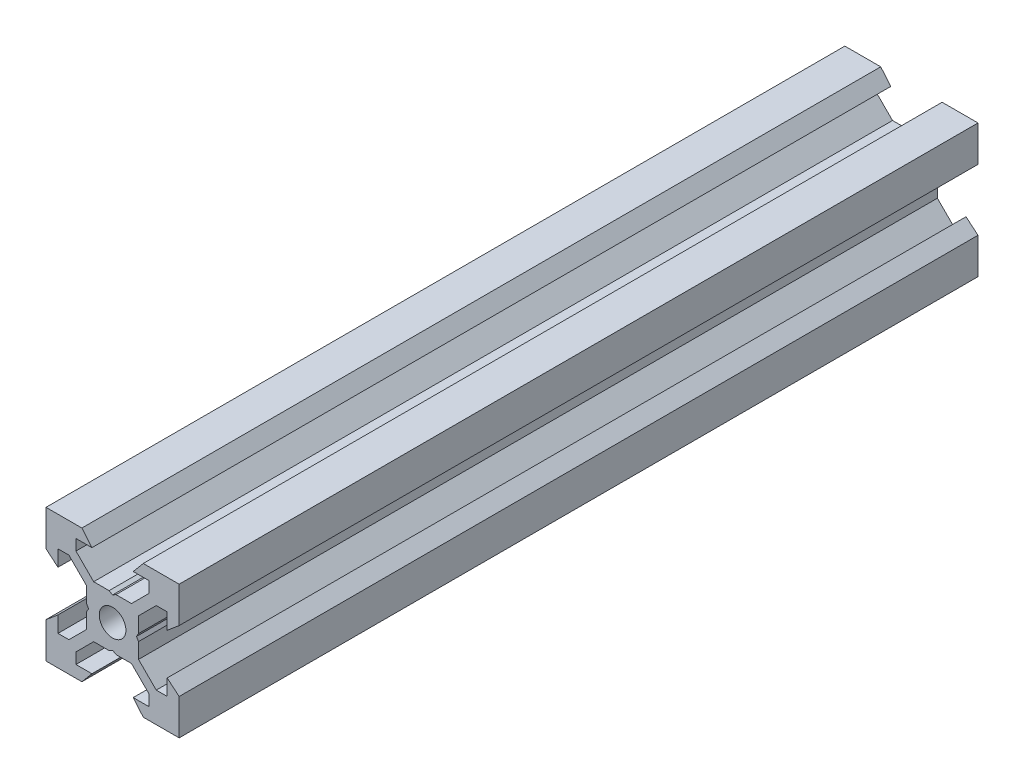
SolidWorks part; units mm, degrees
material "6063-O"
ref_plane "Front Plane" through (0, 0, 0) normal (0, 0, 1) x (1, 0, 0)
ref_plane "Top Plane" through (0, 0, 0) normal (0, 1, 0) x (1, 0, 0)
ref_plane "Right Plane" through (0, 0, 0) normal (1, 0, 0) x (0, 0, -1)
sketch "Sketch1" plane through (0, 0, 0) normal (0, 0, 1) x (1, 0, 0)
  line L0 (10, 10) -> (4.6104, 10) construction
  line L1 (10, 10) -> (10, 4.6104) construction
  line L2 (10, -10) -> (10, -4.6104) construction
  line L3 (10, -10) -> (4.6104, -10) construction
  line L4 (10, 10) -> (10, 4.6104)
  line L5 (6.5607, 5.5) -> (8.2, 5.5)
  line L6 (5.5, 8.2) -> (5.5, 6.5607)
  line L7 (10, 10) -> (4.6104, 10)
  line L8 (10, 10) -> (10, 4.6104)
  line L9 (6.5607, 5.5) -> (3.9, 2.8393)
  line L10 (5.5, 6.5607) -> (2.8393, 3.9)
  line L11 (10, 4.6104) -> (8.2, 3.1)
  line L12 (4.6104, 10) -> (3.1, 8.2)
  line L13 (8.2, 3.1) -> (8.2, 5.5)
  line L14 (3.1, 8.2) -> (5.5, 8.2)
  line L15 (-6.5607, 5.5) -> (-8.2, 5.5)
  line L16 (6.5607, -5.5) -> (8.2, -5.5)
  line L17 (3.1, -8.2) -> (5.5, -8.2)
  line L18 (8.2, -3.1) -> (8.2, -5.5)
  line L19 (4.6104, -10) -> (3.1, -8.2)
  line L20 (10, -4.6104) -> (8.2, -3.1)
  line L21 (0.5196, -3.9) -> (0, -3.6)
  line L22 (0.5196, 3.9) -> (0, 3.6)
  line L23 (3.6, 0) -> (3.9, -0.5196)
  line L24 (3.9, 0.5196) -> (3.6, 0)
  line L25 (3.9, 0.5196) -> (3.9, 2.8393)
  line L26 (2.8393, 3.9) -> (0.5196, 3.9)
  line L27 (3.9, -2.8393) -> (3.9, -0.5196)
  line L28 (2.8393, -3.9) -> (0.5196, -3.9)
  line L29 (5.5, -6.5607) -> (2.8393, -3.9)
  line L30 (6.5607, -5.5) -> (3.9, -2.8393)
  line L31 (10, -10) -> (10, -4.6104)
  line L32 (10, -10) -> (4.6104, -10)
  line L33 (5.5, -8.2) -> (5.5, -6.5607)
  line L34 (-6.5607, -5.5) -> (-8.2, -5.5)
  line L35 (10, -10) -> (10, -4.6104)
  line L36 (0, 0) -> (0, 8.2) construction
  line L37 (-10, -10) -> (-4.6104, -10) construction
  line L38 (-10, -10) -> (-10, -4.6104) construction
  line L39 (-10, 10) -> (-10, 4.6104) construction
  line L40 (-10, 10) -> (-4.6104, 10) construction
  line L41 (-10, -10) -> (-10, -4.6104)
  line L43 (-5.5, -8.2) -> (-5.5, -6.5607)
  line L44 (-10, -10) -> (-4.6104, -10)
  line L45 (-10, -10) -> (-10, -4.6104)
  line L46 (-6.5607, -5.5) -> (-3.9, -2.8393)
  line L47 (-5.5, -6.5607) -> (-2.8393, -3.9)
  line L48 (-2.8393, -3.9) -> (-0.5196, -3.9)
  line L49 (-3.9, -2.8393) -> (-3.9, -0.5196)
  line L50 (-2.8393, 3.9) -> (-0.5196, 3.9)
  line L51 (-3.9, 0.5196) -> (-3.9, 2.8393)
  line L52 (-3.9, 0.5196) -> (-3.6, 0)
  line L53 (-3.6, 0) -> (-3.9, -0.5196)
  line L54 (-0.5196, 3.9) -> (0, 3.6)
  line L55 (-0.5196, -3.9) -> (0, -3.6)
  line L56 (-10, -4.6104) -> (-8.2, -3.1)
  line L57 (-4.6104, -10) -> (-3.1, -8.2)
  line L58 (-8.2, -3.1) -> (-8.2, -5.5)
  line L59 (-3.1, -8.2) -> (-5.5, -8.2)
  line L60 (-10, -10) -> (10, -10) construction
  line L61 (-10, -10) -> (-10, 10) construction
  line L62 (-3.1, 8.2) -> (-5.5, 8.2)
  line L63 (-8.2, 3.1) -> (-8.2, 5.5)
  line L64 (-4.6104, 10) -> (-3.1, 8.2)
  line L65 (-10, 4.6104) -> (-8.2, 3.1)
  line L66 (-5.5, 6.5607) -> (-2.8393, 3.9)
  line L67 (-6.5607, 5.5) -> (-3.9, 2.8393)
  line L68 (-10, 10) -> (-10, 4.6104)
  line L69 (-10, 10) -> (-4.6104, 10)
  line L70 (-5.5, 8.2) -> (-5.5, 6.5607)
  line L71 (-10, 10) -> (10, 10) construction
  line L72 (-10, 10) -> (-10, 4.6104)
  line L73 (10, -10) -> (10, 10) construction
  line L74 (-10, -10) -> (10, 10) construction
  line L75 (-10, 10) -> (10, -10) construction
  circle A0 centre (0, 0) radius 2
  dimension "D7" = 4
  dimension "D1" = 20
  dimension "D2" = 5.3896
  dimension "D3" = 4.5
  dimension "D4" = 50
  dimension "D5" = 1.8
  dimension "D6" = 1.5104
  dimension "D8" = 5.5
  dimension "D9" = 120
  dimension "D10" = 0.3
  dimension "D11" = 2.3197
  dimension "D12" = 7.8
  dimension "D13" = 7.8
  dimension "D14" = 1.5
  dimension "D15" = 2.6607
extrude "Boss-Extrude1" add sketch "Sketch1" along normal mid plane 120 contours L70 L62 L64 L69 L68 L65 L63 L15 L67 L51 L52 L53 L49 L46 L34 L58 L56 L41 L44 L57 L59 L43 L47 L48 L55 L21 L28 L29 L33 L17 L19 L32 L31 L20 L18 L16 L30 L27 L23 L24 L25 L9 L5 L13 L11 L4 L7 L12 L14 L6 L10
